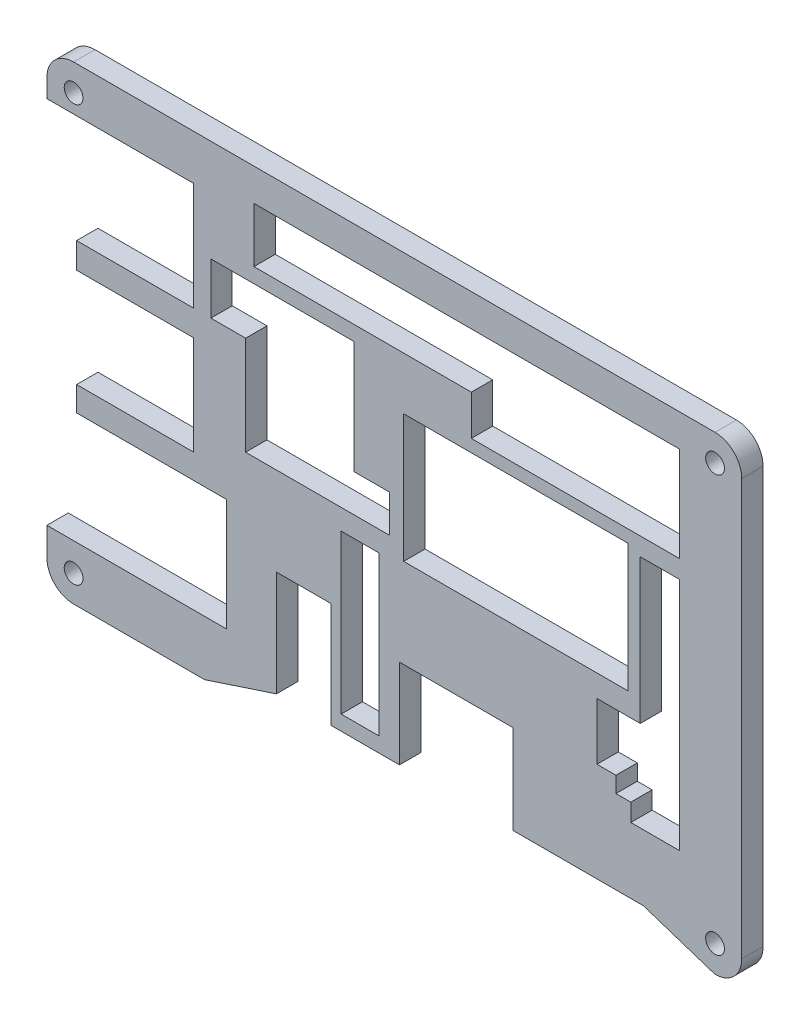
SolidWorks part; units mm, degrees
ref_plane "Front Plane" through (0, 0, 0) normal (0, 0, 1) x (1, 0, 0)
ref_plane "Top Plane" through (0, 0, 0) normal (0, 1, 0) x (1, 0, 0)
ref_plane "Right Plane" through (0, 0, 0) normal (1, 0, 0) x (0, 0, -1)
sketch "Sketch2" plane through (0, 0, 8.1718) normal (0, 0, -1) x (-1, 0, 0)
  line L0 (-23.8449, -33.0844) -> (-34.0849, -36.451) construction
  line L1 (-37.8949, -32.641) -> (-37.8949, 26.6977) construction
  line L2 (-34.0849, 30.5077) -> (57.4049, 30.5077) construction
  line L3 (61.2149, 26.6839) -> (61.2149, 24.0683) construction
  line L4 (56.975, 8.6582) -> (56.975, 4.9979) construction
  line L5 (56.975, -9.1218) -> (56.975, -12.628) construction
  line L6 (61.2149, -28.6278) -> (61.2149, -32.6134) construction
  line L7 (38.7143, -36.451) -> (57.405, -36.451) construction
  line L8 (28.4743, -33.0844) -> (38.7143, -36.451) construction
  line L9 (-23.8449, -33.0844) -> (-34.0849, -36.451)
  line L10 (-37.8949, -32.641) -> (-37.8949, 26.6977)
  line L11 (-34.0849, 30.5077) -> (57.4049, 30.5077)
  line L12 (61.2149, 26.6839) -> (61.2149, 24.0683)
  line L13 (56.975, 8.6582) -> (56.975, 4.9979)
  line L14 (56.975, -9.1218) -> (56.975, -12.628)
  line L15 (61.2149, -28.6278) -> (61.2149, -32.6134)
  line L16 (38.7143, -36.451) -> (57.405, -36.451)
  line L17 (28.4743, -33.0844) -> (38.7143, -36.451)
  line L18 (-23.8449, -33.0844) -> (-5.3029, -33.0844)
  line L19 (-5.3029, -33.0844) -> (-5.3029, -20.3844)
  line L20 (-5.3029, -20.3844) -> (10.9264, -20.3844)
  line L21 (10.9264, -16.0062) -> (10.9264, -22.1276) construction
  line L22 (10.9264, -20.3844) -> (10.9264, -33.0844)
  line L23 (10.9264, -33.0844) -> (20.6581, -33.0844)
  line L24 (20.6581, -33.0844) -> (20.6581, -18.0349)
  line L25 (20.6581, -18.0349) -> (28.4743, -18.0349)
  line L26 (28.4743, -18.0349) -> (28.4743, -33.0844)
  line L27 (13.845, -30.9668) -> (19.2484, -30.9668)
  line L28 (20.6581, -30.9668) -> (13.845, -30.9668) construction
  line L29 (19.2484, -30.9668) -> (19.2484, -8.3602)
  line L30 (19.2484, -8.3602) -> (13.845, -8.3602)
  line L31 (13.845, -8.3602) -> (13.845, -30.9668)
  line L32 (-29.0049, -23.6989) -> (-22.0669, -23.6989) construction
  line L33 (-22.0669, -21.1858) -> (-22.0669, -23.6989) construction
  line L34 (-19.9509, -21.1858) -> (-22.0669, -21.1858) construction
  line L35 (-19.9509, -18.9206) -> (-19.9509, -21.1858) construction
  line L36 (-17.2447, -18.9206) -> (-19.9509, -18.9206) construction
  line L37 (-17.2447, -10.7926) -> (-17.2447, -18.9206) construction
  line L38 (-23.4169, -10.7926) -> (-17.2447, -10.7926) construction
  line L39 (-23.4169, 9.8012) -> (-23.4169, -10.7926) construction
  line L40 (-29.0049, 9.8012) -> (-29.0049, -23.6989) construction
  line L41 (-23.4169, 9.8012) -> (-29.0049, 9.8012) construction
  line L42 (-29.0049, -23.6989) -> (-22.0669, -23.6989)
  line L43 (-22.0669, -21.1858) -> (-22.0669, -23.6989)
  line L44 (-19.9509, -21.1858) -> (-22.0669, -21.1858)
  line L45 (-19.9509, -18.9206) -> (-19.9509, -21.1858)
  line L46 (-17.2447, -18.9206) -> (-19.9509, -18.9206)
  line L47 (-17.2447, -10.7926) -> (-17.2447, -18.9206)
  line L48 (-23.4169, -10.7926) -> (-17.2447, -10.7926)
  line L49 (-23.4169, 9.8012) -> (-23.4169, -10.7926)
  line L50 (-29.0049, 9.8012) -> (-29.0049, -23.6989)
  line L51 (-23.4169, 9.8012) -> (-29.0049, 9.8012)
  line L52 (-21.6389, 10.5941) -> (-21.6389, -7.643) construction
  line L53 (-21.6389, 10.5941) -> (10.329, 10.5941) construction
  line L54 (12.361, -0.0976) -> (17.441, -0.0976) construction
  line L55 (12.361, -0.0976) -> (12.361, -5.4315) construction
  line L56 (37.825, 8.6582) -> (32.872, 8.6582) construction
  line L57 (37.825, 15.9724) -> (37.825, 8.6582) construction
  line L58 (17.441, 15.9724) -> (37.825, 15.9724) construction
  line L59 (17.441, 15.9724) -> (17.441, -0.0976) construction
  line L60 (-21.6389, 10.5941) -> (-21.6389, -7.643)
  line L61 (-21.6389, 10.5941) -> (10.329, 10.5941)
  line L62 (12.361, -0.0976) -> (17.441, -0.0976)
  line L63 (12.361, -0.0976) -> (12.361, -5.4315)
  line L64 (37.825, 8.6582) -> (32.872, 8.6582)
  line L65 (37.825, 15.9724) -> (37.825, 8.6582)
  line L66 (17.441, 15.9724) -> (37.825, 15.9724)
  line L67 (17.441, 15.9724) -> (17.441, -0.0976)
  line L68 (32.872, 8.6582) -> (32.872, -5.4315)
  line L69 (12.361, -5.4315) -> (33.38, -5.4315) construction
  line L70 (32.872, -5.4315) -> (12.361, -5.4315)
  line L71 (-21.6389, -7.643) -> (10.329, -7.643)
  line L72 (10.329, 10.5941) -> (10.329, -9.6302) construction
  line L73 (10.329, -7.643) -> (10.329, 10.5941)
  line L74 (0.6771, 12.3721) -> (-29.0048, 12.3721)
  line L75 (-29.0049, 25.897) -> (-29.0048, 12.0872) construction
  line L76 (-29.0048, 12.3721) -> (-29.0049, 25.897)
  line L77 (-29.0049, 25.897) -> (31.6883, 25.897)
  line L78 (31.6883, 25.897) -> (31.6883, 18.087)
  line L79 (31.6883, 18.087) -> (0.6771, 18.087)
  line L80 (0.6771, 18.087) -> (0.6771, 12.3721)
  line L81 (56.975, 8.6582) -> (40.325, 8.6582)
  line L82 (40.325, 8.6582) -> (40.325, 24.0683)
  line L83 (40.325, 24.0683) -> (61.2149, 24.0683)
  line L84 (56.975, 4.9979) -> (40.325, 4.9979)
  line L85 (40.325, 4.9979) -> (40.325, -9.1218)
  line L86 (35.285, -9.1218) -> (56.975, -9.1218) construction
  line L87 (40.325, -9.1218) -> (56.975, -9.1218)
  line L88 (61.2149, -28.6278) -> (35.575, -28.6278)
  line L89 (35.575, -28.6278) -> (35.575, -12.628)
  line L90 (56.975, -12.628) -> (33.9353, -12.628) construction
  line L91 (35.575, -12.628) -> (56.975, -12.628)
  arc A0 (-37.8949, -32.641) -> (-34.0849, -36.451) centre (-34.0849, -32.641) ccw construction
  arc A1 (-34.0849, 30.5077) -> (-37.8949, 26.6977) centre (-34.0849, 26.6977) ccw construction
  arc A2 (61.2149, 26.6839) -> (57.4049, 30.5077) centre (57.4049, 26.6977) ccw construction
  arc A3 (57.405, -36.451) -> (61.2149, -32.6134) centre (57.405, -32.641) ccw construction
  arc A4 (-37.8949, -32.641) -> (-34.0849, -36.451) centre (-34.0849, -32.641) ccw
  arc A5 (-34.0849, 30.5077) -> (-37.8949, 26.6977) centre (-34.0849, 26.6977) ccw
  arc A6 (61.2149, 26.6839) -> (57.4049, 30.5077) centre (57.4049, 26.6977) ccw
  arc A7 (57.405, -36.451) -> (61.2149, -32.6134) centre (57.405, -32.641) ccw
  dimension "D1" = 12.7
  dimension "D2" = 1.4097
  dimension "D3" = 15.0495
extrude "Boss-Extrude1" add sketch "Sketch2" along normal blind 3.048
sketch "Sketch3" plane through (0, 0, 5.1238) normal (0, 0, -1) x (-1, 0, 0)
  circle A0 centre (57.405, -32.641) radius 1.3382
  circle A1 centre (-34.0849, -32.641) radius 1.3382
  circle A2 centre (-34.0849, 26.6977) radius 1.3382
  circle A3 centre (57.4049, 26.6977) radius 1.3382
  dimension "D1" = 2.6765
extrude "Cut-Extrude1" cut sketch "Sketch3" against normal through all
